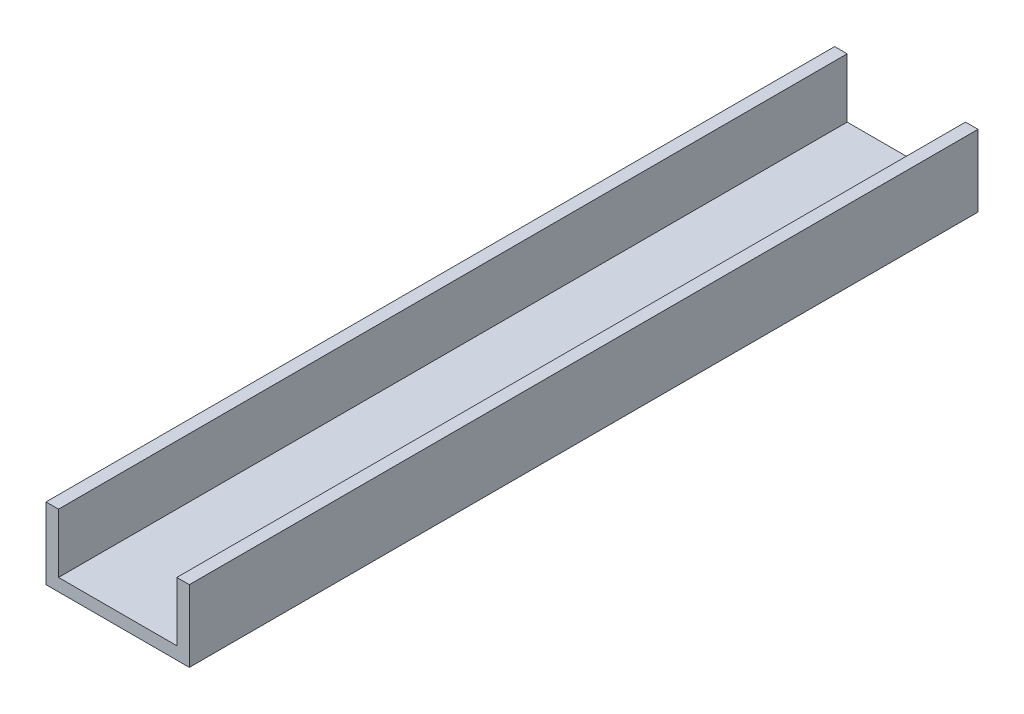
SolidWorks part; units mm, degrees
material "Oak"
ref_plane "Front Plane" through (0, 0, 0) normal (0, 0, 1) x (1, 0, 0)
ref_plane "Top Plane" through (0, 0, 0) normal (0, 1, 0) x (1, 0, 0)
ref_plane "Right Plane" through (0, 0, 0) normal (1, 0, 0) x (0, 0, -1)
sketch "Sketch1" plane through (0, 0, 0) normal (1, 0, 0) x (0, 0, -1)
  line L1 (0, 0) -> (200, 0)
  line L2 (0, 0) -> (0, 3.175)
  line L3 (0, 3.175) -> (200, 3.175)
  line L4 (200, 0) -> (200, 3.175)
  dimension "D1" = 3.175
  dimension "D2" = 200
extrude "Boss-Extrude1" add sketch "Sketch1" along normal blind 36.35
sketch "Sketch2" plane through (0, 3.175, 0) normal (0, 1, 0) x (1, 0, 0)
  line L0 (36.35, 0) -> (0, 0) construction
  line L1 (0, 200) -> (3.175, 200)
  line L2 (0, 200) -> (0, 0)
  line L3 (0, 0) -> (3.175, 0)
  line L4 (3.175, 200) -> (3.175, 0)
  line L6 (36.35, 200) -> (33.175, 200)
  line L7 (36.35, 200) -> (36.35, 0)
  line L8 (36.35, 0) -> (33.175, 0)
  line L9 (33.175, 200) -> (33.175, 0)
  dimension "D1" = 3.175
  dimension "D2" = 3.175
extrude "Boss-Extrude2" add sketch "Sketch2" along normal blind 15
